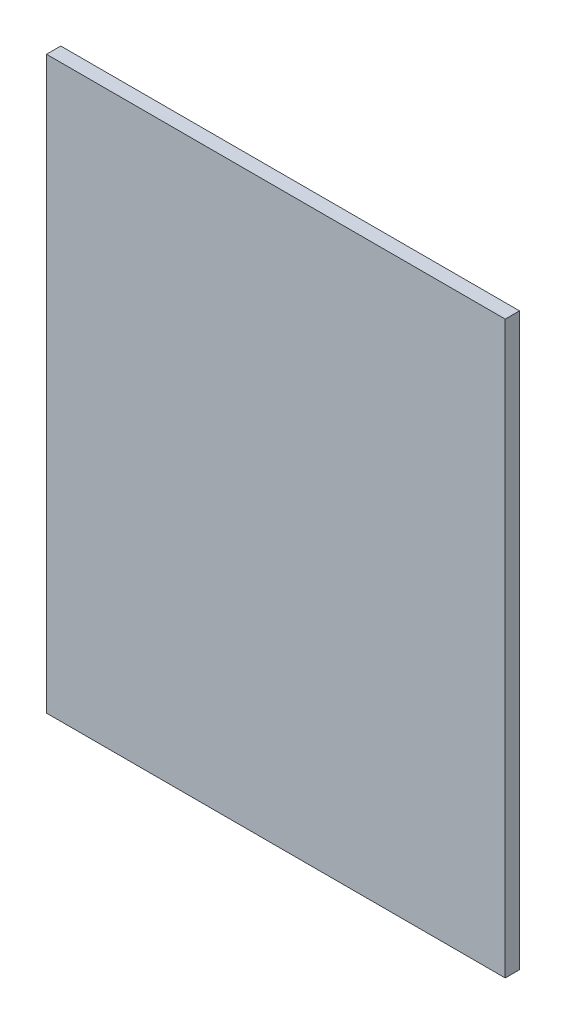
SolidWorks part; units mm, degrees
ref_plane "Спереди" through (0, 0, 0) normal (0, 0, 1) x (1, 0, 0)
ref_plane "Сверху" through (0, 0, 0) normal (0, 1, 0) x (1, 0, 0)
ref_plane "Справа" through (0, 0, 0) normal (1, 0, 0) x (0, 0, -1)
sketch "Эскиз1" plane through (0, 0, 0) normal (0, 1, 0) x (1, 0, 0)
  line L1 (-0.4766, -8.7409) -> (79.9136, -8.7409)
  line L2 (-0.4766, -8.7409) -> (-0.4766, -11.2409)
  line L3 (-0.4766, -11.2409) -> (79.9136, -11.2409)
  line L4 (79.9136, -8.7409) -> (79.9136, -11.2409)
extrude "Вытянуть1" add sketch "Эскиз1" along normal blind 100
